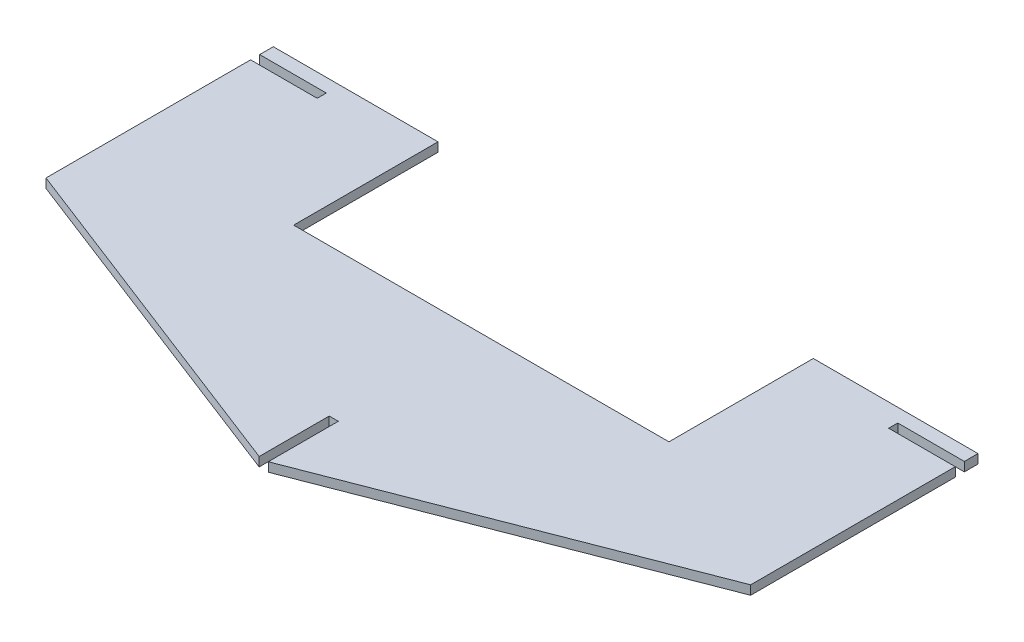
SolidWorks part; units mm, degrees
ref_plane "Front Plane" through (0, 0, 0) normal (0, 0, 1) x (1, 0, 0)
ref_plane "Top Plane" through (0, 0, 0) normal (0, 1, 0) x (1, 0, 0)
ref_plane "Right Plane" through (0, 0, 0) normal (1, 0, 0) x (0, 0, -1)
sketch "Sketch1" plane through (0, 0, 0) normal (0, 1, 0) x (1, 0, 0)
  line L0 (0, -100) -> (155, -160)
  line L1 (0, 0) -> (310, 0)
  line L2 (0, 0) -> (0, -100)
  line L3 (0, -100) -> (310, -100)
  line L4 (310, 0) -> (310, -100)
  line L5 (155, -160) -> (310, -100)
  line L6 (155, -160) -> (155, -100) construction
  line L7 (0, -6) -> (29.3, -6)
  line L8 (0, -6) -> (0, -10)
  line L9 (0, -10) -> (29.3, -10)
  line L10 (29.3, -6) -> (29.3, -10)
  line L15 (153, -160) -> (157, -160)
  line L16 (153, -160) -> (153, -128.4)
  line L17 (153, -128.4) -> (157, -128.4)
  line L18 (157, -160) -> (157, -128.4)
  line L19 (310, -6) -> (310, -10)
  line L20 (310, -10) -> (280.7, -10)
  line L21 (280.7, -6) -> (280.7, -10)
  line L22 (310, -6) -> (280.7, -6)
  point P19 (155, -160)
  dimension "D1" = 310
  dimension "D2" = 100
  dimension "D3" = 60
  dimension "D4" = 29.3
  dimension "D5" = 4
  dimension "D6" = 6
  dimension "D7" = 31.6
extrude "Boss-Extrude1" add sketch "Sketch1" along normal blind 4 contours L0 L6 L3 | L4 L1 L2 L3 | L6 L5 L3
ref_plane "Plane1" through (155, 0, 0) normal (-1, 0, 0) x (0, 0, 1)
sketch "Sketch2" plane through (0, 4, 0) normal (0, 1, 0) x (1, 0, 0)
  line L0 (0, 0) -> (310, 0) construction
  line L1 (72.45, 0) -> (237.55, 0)
  line L2 (72.45, 0) -> (72.45, -63.5)
  line L3 (72.45, -63.5) -> (237.55, -63.5)
  line L4 (237.55, 0) -> (237.55, -63.5)
  line L5 (155, 2.2) -> (155, -2.2) construction
  point P6 (155, 0)
  dimension "D1" = 165.1
  dimension "D2" = 63.5
extrude "Cut-Extrude1" cut sketch "Sketch2" against normal through all
